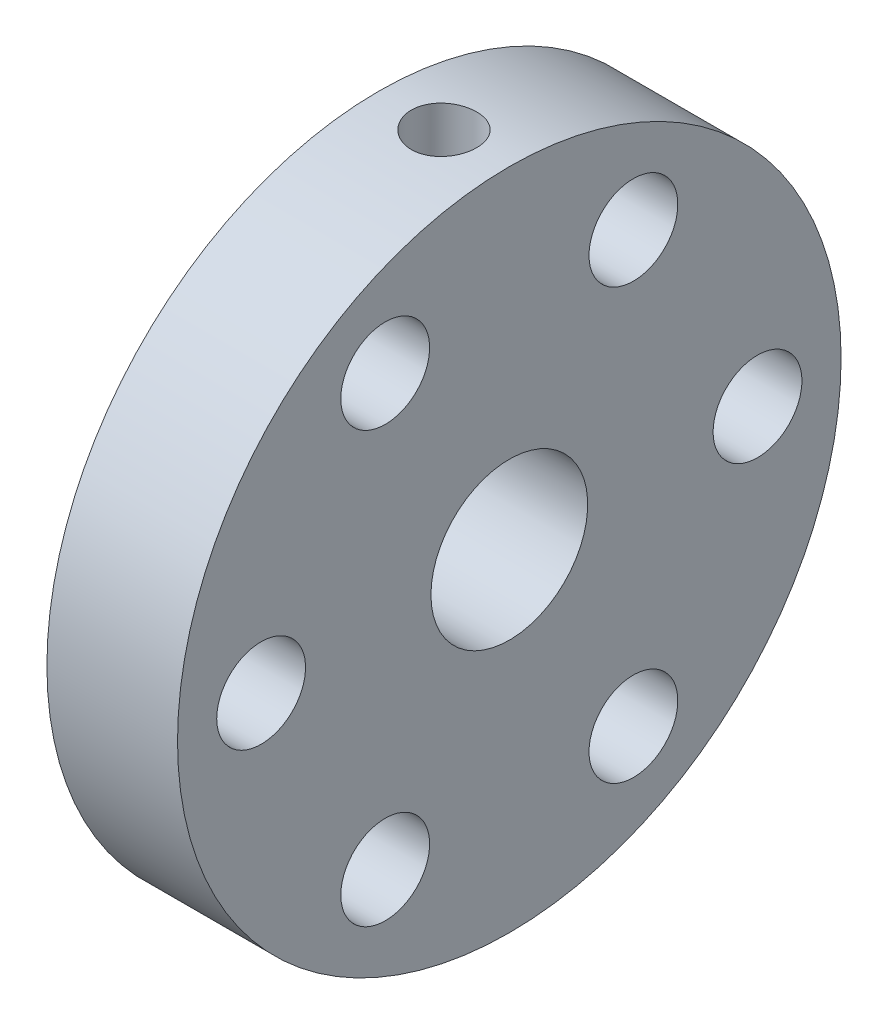
SolidWorks part; units mm, degrees
ref_plane "Plan de face" through (0, 0, 0) normal (0, 0, 1) x (1, 0, 0)
ref_plane "Plan de dessus" through (0, 0, 0) normal (0, 1, 0) x (1, 0, 0)
ref_plane "Plan de droite" through (0, 0, 0) normal (1, 0, 0) x (0, 0, -1)
sketch "Esquisse1" plane through (0, 0, 0) normal (0, 0, 1) x (1, 0, 0)
  line L0 (0, 0) -> (5.6653, 0) construction
  line L1 (0, 0) -> (0, -2.5904) construction
  line L3 (0, 3) -> (5, 3)
  line L4 (0, 3) -> (0, 12.7)
  line L5 (0, 12.7) -> (5, 12.7)
  line L6 (5, 3) -> (5, 12.7)
  line L7 (0, 3) -> (-4.2, 3)
  line L8 (0, 3) -> (0, 6)
  line L9 (0, 6) -> (-4.2, 6)
  line L10 (-4.2, 3) -> (-4.2, 6)
  dimension "D1" = 3
  dimension "D2" = 12.7
  dimension "D3" = 6
  dimension "D4" = 4.2
  dimension "D5" = 5
revolve "Révolution1" add sketch "Esquisse1" angle 360 about L0
hole_wizard "Dégagement M31" positions "Esquisse3" profile "Esquisse2" hole size "M3" standard "Ansi Metric" end condition through all
sketch "Esquisse3" plane through (0, 0, 0) normal (-1, 0, 0) x (0, 0, 1)
  line L1 (4.75, 8.2272) -> (-4.75, 8.2272)
  line L2 (-4.75, 8.2272) -> (-9.5, 0)
  line L3 (-9.5, 0) -> (-4.75, -8.2272)
  line L4 (-4.75, -8.2272) -> (4.75, -8.2272)
  line L5 (4.75, -8.2272) -> (9.5, 0)
  line L6 (9.5, 0) -> (4.75, 8.2272)
  line L7 (0, 0) -> (0, 15.3598) construction
  circle A0 centre (0, 0) radius 9.5
  circle A1 centre (0, 0) radius 8.2272 construction
  point P8 (4.75, 8.2272)
  point P9 (-4.75, 8.2272)
  point P10 (-9.5, 0)
  point P11 (-4.75, -8.2272)
  point P12 (4.75, -8.2272)
  point P13 (9.5, 0)
  dimension "D1" = 19
sketch "Esquisse2" plane through (0, 8.2272, 4.75) normal (0, 1, 0) x (0, 0, 1)
  line L0 (0, 0) -> (0, 5)
  line L1 (0, 5) -> (1.7, 5)
  line L2 (1.7, 5) -> (1.7, 0)
  line L5 (1.7, 0) -> (0, 0)
  line L11 (0, -6.35) -> (0, 107.95) construction
  dimension "Diamètre du perçage jusqu'au prochain" = 3.4
  dimension "Profondeur du perçage jusqu'au prochain" = 5
hole_wizard "Trou pour taraudage pour trou taraudé M3x0.51" positions "Esquisse5" profile "Esquisse4" hole size "M3x0.5" standard "Ansi Metric"
sketch "Esquisse5" plane through (0, 0, 0) normal (0, 1, 0) x (1, 0, 0)
  line L0 (0, 0) -> (9.1746, 0) construction
  line L13 (-4.2, 0) -> (-2.1, 0)
  line L14 (-2.1, 0) -> (0, 0)
  line L15 (0, 0) -> (2.5, 0)
  line L16 (2.5, 0) -> (5, 0)
  point P0 (2.5, 0)
  point P2 (-2.1, 0)
  dimension "D1" = 2.1
  dimension "D2" = 2.5
sketch "Esquisse4" plane through (2.5, 0, 0) normal (1, 0, 0) x (0, 0, -1)
  line L0 (0, 0) -> (0, 12.7)
  line L1 (0, 12.7) -> (1.25, 12.7)
  line L2 (1.25, 12.7) -> (1.25, 0)
  line L5 (1.25, 0) -> (0, 0)
  line L11 (0, -6.35) -> (0, 107.95) construction
  dimension "Diamètre du perçage jusqu'au prochain" = 2.5
  dimension "Profondeur du perçage jusqu'au prochain" = 12.7
